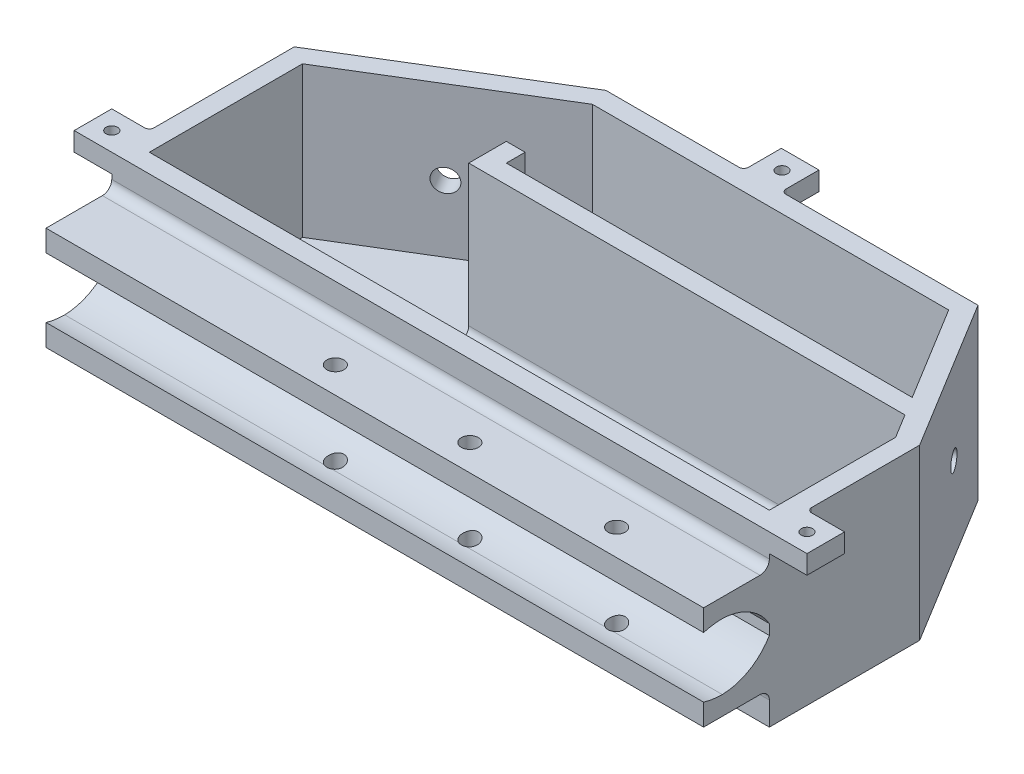
SolidWorks part; units mm, degrees
ref_plane "Front Plane" through (0, 0, 0) normal (0, 0, 1) x (1, 0, 0)
ref_plane "Top Plane" through (0, 0, 0) normal (0, 1, 0) x (1, 0, 0)
ref_plane "Right Plane" through (0, 0, 0) normal (1, 0, 0) x (0, 0, -1)
sketch "Sketch1" plane through (0, 0, 0) normal (0, 1, 0) x (1, 0, 0)
  line L1 (-165, 70) -> (165, 70)
  line L2 (-165, 70) -> (-165, -70)
  line L3 (-165, -70) -> (165, -70)
  line L4 (165, 70) -> (165, -70)
  line L5 (-165, 70) -> (165, -70) construction
  line L6 (-165, -70) -> (165, 70) construction
  line L7 (-175, 80) -> (175, 80)
  line L8 (-175, 80) -> (-175, -80)
  line L9 (-175, -80) -> (175, -80)
  line L10 (175, 80) -> (175, -80)
  line L11 (-175, 80) -> (175, -80) construction
  line L12 (-175, -80) -> (175, 80) construction
  point P0 (0, 0)
  point P6 (0, 0)
  dimension "D1" = 330
  dimension "D2" = 140
  dimension "D3" = 350
  dimension "D4" = 160
extrude "Boss-Extrude1" add sketch "Sketch1" along normal blind 80
sketch "Sketch2" plane through (0, 0, 0) normal (0, -1, 0) x (1, 0, 0)
  line L1 (-175, 80) -> (175, 80)
  line L2 (-175, 80) -> (-175, -80)
  line L3 (-175, -80) -> (175, -80)
  line L4 (175, 80) -> (175, -80)
  line L5 (-175, 80) -> (175, -80) construction
  line L6 (-175, -80) -> (175, 80) construction
  point P0 (0, 0)
extrude "Boss-Extrude2" add sketch "Sketch2" along normal blind 10
sketch "Sketch3" plane through (0, 0, 0) normal (0, 1, 0) x (1, 0, 0)
  line L0 (-165, -70) -> (165, -70) construction
  line L1 (-75, 20) -> (165, 20)
  line L2 (-75, 20) -> (-75, 10)
  line L3 (-75, 10) -> (165, 10)
  line L4 (165, 20) -> (165, 10)
  line L5 (165, -70) -> (165, 70) construction
  dimension "D1" = 240
  dimension "D2" = 10
  dimension "D3" = 80
  dimension "D4" = 0
extrude "Boss-Extrude3" add sketch "Sketch3" along normal up to vertex (80 mm away)
sketch "Sketch4" plane through (0, -10, 0) normal (0, -1, 0) x (1, 0, 0)
  line L0 (165, -70) -> (-165, -70) construction
  line L1 (165, -20) -> (165, -70) construction
  circle A0 centre (115, -45) radius 8.25
  dimension "D1" = 16.5
  dimension "D2" = 25
  dimension "D3" = 50
extrude "Cut-Extrude1" cut sketch "Sketch4" against normal blind 10
sketch "Sketch5" plane through (0, 0, -20) normal (0, 0, -1) x (-1, 0, 0)
  line L0 (-165, 0) -> (75, 0) construction
  line L1 (75, 80) -> (65, 80)
  line L2 (75, 80) -> (75, 0)
  line L3 (75, 0) -> (65, 0)
  line L4 (65, 80) -> (65, 0)
  dimension "D1" = 10
extrude "Boss-Extrude4" add sketch "Sketch5" along normal blind 10
sketch "Sketch6" plane through (-175, 0, 0) normal (-1, 0, 0) x (0, 0, 1)
  line L0 (80, 80) -> (80, -10) construction
  line L1 (80, 62.5) -> (115, 62.5)
  line L2 (80, 62.5) -> (80, 7.5)
  line L3 (80, 7.5) -> (115, 7.5)
  line L4 (115, 62.5) -> (115, 7.5)
  point P9 (80, 35)
  point P10 (80, 35)
  dimension "D1" = 35
  dimension "D2" = 55
extrude "Boss-Extrude5" add sketch "Sketch6" against normal up to vertex (350 mm away)
sketch "Sketch7" plane through (-175, 0, 0) normal (-1, 0, 0) x (0, 0, 1)
  line L0 (115, 62.5) -> (80, 7.5) construction
  line L1 (80, 62.5) -> (115, 7.5) construction
  line L2 (97.5, 35) -> (80, 35) construction
  line L3 (80, 62.5) -> (80, 7.5) construction
  line L4 (80, 32.25) -> (80, 37.75)
  arc A0 (80, 32.25) -> (105.0363, 17.552) centre (105.81, 47.542) ccw
  arc A1 (80, 37.75) -> (104.9636, 52.5519) centre (105.8735, 22.5657) cw
  ellipse E0 centre (104.9999, 35.052) end of major axis (80, 35) minor radius 17.5 (105.0363, 17.552) -> (104.9636, 52.5519) ccw
  point P21 (80, 35)
  dimension "D1" = 50
  dimension "D2" = 35
  dimension "D3" = 5.5
extrude "Cut-Extrude2" cut sketch "Sketch7" against normal through all
sketch "Sketch8" plane through (0, 62.5, 0) normal (0, 1, 0) x (1, 0, 0)
  line L1 (-175, -80) -> (-175, -115) construction
  line L4 (175, -101) -> (-175, -101) construction
  line L5 (175, -115) -> (175, -80) construction
  line L6 (-175, -115) -> (-175, -80) construction
  line L7 (175, -80) -> (-175, -80) construction
  circle A0 centre (-35, -101) radius 4.55
  circle A1 centre (36.6, -101) radius 4.55
  circle A2 centre (114.7, -101) radius 4.55
  dimension "D1" = 9.1
  dimension "D2" = 9.1
  dimension "D3" = 9.1
  dimension "D4" = 21
  dimension "D5" = 71.6
  dimension "D6" = 78.1
  dimension "D7" = 140
extrude "Cut-Extrude3" cut sketch "Sketch8" against normal through all
sketch "Sketch9" plane through (0, 80, 0) normal (0, 1, 0) x (1, 0, 0)
  line L0 (0, 0) -> (0, 80) construction
  line L7 (-175, 80) -> (-175, -80) construction
  line L23 (175, 80) -> (-175, 80) construction
  line L24 (0, 0) -> (175, 0) construction
  line L25 (175, -80) -> (175, 80) construction
  line L30 (175, -80) -> (195, -80)
  line L31 (175, -80) -> (175, -60)
  line L32 (175, -60) -> (195, -60)
  line L33 (195, -80) -> (195, -60)
  line L34 (-195, -80) -> (-195, -60)
  line L35 (-175, -60) -> (-195, -60)
  line L36 (-175, -80) -> (-175, -60)
  line L37 (-175, -80) -> (-195, -80)
  circle A3 centre (185, -70) radius 3.05
  circle A4 centre (-185, -70) radius 3.05
  dimension "D4" = 0
  dimension "D5" = 10
extrude "Boss-Extrude7" add sketch "Sketch9" against normal blind 10
fillet "Fillet1" radius 5 4 edges at (0, 7.5, 80) (0, 62.5, 80) (45, 0, -10) (50, 0, -20)
sketch "Sketch12" plane through (0, 80, 0) normal (0, 1, 0) x (1, 0, 0)
  line L0 (-72.0151, 80) -> (-175, 17.1383)
  line L1 (175, 80) -> (-175, 80) construction
  line L2 (-175, 80) -> (-175, -60) construction
  line L3 (-175, 17.1383) -> (-175, 80)
  line L4 (-175, 80) -> (-72.0151, 80)
  line L5 (175, 80) -> (-175, 80) construction
  point P6 (-175, -40.1221)
  point P9 (-81.3581, 80)
  point P12 (-175, -32.0879)
  point P13 (-90.837, 80)
  point P14 (-175, 17.1383)
  point P15 (-81.4726, 80)
  point P16 (0, 0)
  point P17 (-72.0151, 80)
extrude "Cut-Extrude5" cut sketch "Sketch12" against normal through all
sketch "Sketch13" plane through (-55.1248, 0, -90.3098) normal (-0.521, 0, -0.8536) x (-0.8536, 0, 0.521)
  line L1 (19.7882, -10) -> (140.4426, -10)
  line L2 (19.7882, -10) -> (19.7882, 80)
  line L3 (19.7882, 80) -> (140.4426, 80)
  line L4 (140.4426, -10) -> (140.4426, 80)
extrude "Boss-Extrude8" add sketch "Sketch13" against normal blind 10
sketch "Sketch14" plane through (0, 80, 0) normal (0, 1, 0) x (1, 0, 0)
  line L0 (126.0404, 80) -> (175, 0)
  line L1 (175, 80) -> (-72.0151, 80) construction
  line L2 (175, -60) -> (175, 80) construction
  line L3 (175, 0) -> (175, 80)
  line L4 (175, 80) -> (126.0404, 80)
  line L5 (175, -60) -> (175, 80) construction
  point P6 (175, 38.4785)
  point P10 (175, 36.4408)
  point P11 (126.0404, 80)
  point P12 (175, 20.615)
  point P13 (175, 18.8567)
  point P14 (175, 0)
extrude "Cut-Extrude8" cut sketch "Sketch14" against normal through all
sketch "Sketch15" plane through (127.3155, 0, -77.9165) normal (0.8529, 0, -0.522) x (-0.522, 0, -0.8529)
  line L1 (-91.3498, -10) -> (2.4427, -10)
  line L2 (-91.3498, -10) -> (-91.3498, 80)
  line L3 (-91.3498, 80) -> (2.4427, 80)
  line L4 (2.4427, -10) -> (2.4427, 80)
extrude "Boss-Extrude9" add sketch "Sketch15" against normal blind 10
sketch "Sketch16" plane through (0, 80, 0) normal (0, 1, 0) x (1, 0, 0)
  line L11 (1.381, 80) -> (21.381, 80)
  line L12 (1.381, 80) -> (1.381, 100)
  line L13 (1.381, 100) -> (21.381, 100)
  line L14 (21.381, 80) -> (21.381, 100)
  circle A2 centre (11.718, 90) radius 3.05
  dimension "D8" = 6.1
  dimension "D6" = 20
  dimension "D7" = 20
extrude "Boss-Extrude10" add sketch "Sketch16" against normal blind 10
sketch "Sketch17" plane through (127.3155, 0, -77.9165) normal (0.8529, 0, -0.522) x (-0.522, 0, -0.8529)
  line L0 (-91.3498, -10) -> (-91.3498, 80) construction
  circle A0 centre (-36.3498, 35) radius 5
  dimension "D1" = 10
  dimension "D2" = 55
extrude "Cut-Extrude9" cut sketch "Sketch17" against normal blind 10
sketch "Sketch18" plane through (-55.1248, 0, -90.3098) normal (-0.521, 0, -0.8536) x (-0.8536, 0, 0.521)
  circle A0 centre (79.4943, 35.4233) radius 6
  dimension "D1" = 12
extrude "Cut-Extrude10" cut sketch "Sketch18" against normal blind 10
fillet "Fillet2" radius 2.5 4 edges at (175, 75, 60) (-175, 75, 60) (1.381, 75, -80) (21.381, 75, -80)
sketch "Sketch19" plane through (0, 80, 0) normal (0, 1, 0) x (1, 0, 0)
  line L0 (-175, 17.1383) -> (-175, -57.5) construction
  line L1 (-177.5, -60) -> (-195, -60) construction
  line L2 (-195, -60) -> (-195, -80) construction
  line L3 (-195, -80) -> (195, -80) construction
  line L4 (195, -80) -> (195, -60) construction
  line L5 (195, -60) -> (177.5, -60) construction
  line L6 (175, -57.5) -> (175, 0) construction
  line L7 (126.0404, 80) -> (175, 0) construction
  line L8 (126.0404, 80) -> (23.881, 80) construction
  line L9 (21.381, 82.5) -> (21.381, 100) construction
  line L10 (21.381, 100) -> (1.381, 100) construction
  line L11 (1.381, 100) -> (1.381, 82.5) construction
  line L12 (-1.119, 80) -> (-72.0151, 80) construction
  line L13 (-175, 17.1383) -> (-72.0151, 80) construction
  line L14 (-175, 17.1383) -> (-175, -57.5)
  line L15 (-177.5, -60) -> (-195, -60)
  line L16 (-195, -60) -> (-195, -80)
  line L17 (-195, -80) -> (195, -80)
  line L18 (195, -80) -> (195, -60)
  line L19 (195, -60) -> (177.5, -60)
  line L20 (175, -57.5) -> (175, 0)
  line L21 (126.0404, 80) -> (175, 0)
  line L22 (126.0404, 80) -> (23.881, 80)
  line L23 (21.381, 82.5) -> (21.381, 100)
  line L24 (21.381, 100) -> (1.381, 100)
  line L25 (1.381, 100) -> (1.381, 82.5)
  line L26 (-1.119, 80) -> (-72.0151, 80)
  line L27 (-175, 17.1383) -> (-72.0151, 80)
  arc A0 (-177.5, -60) -> (-175, -57.5) centre (-177.5, -57.5) ccw construction
  circle A1 centre (-185, -70) radius 3.05 construction
  circle A2 centre (185, -70) radius 3.05 construction
  arc A3 (175, -57.5) -> (177.5, -60) centre (177.5, -57.5) ccw construction
  arc A4 (21.381, 82.5) -> (23.881, 80) centre (23.881, 82.5) ccw construction
  circle A5 centre (11.718, 90) radius 3.05 construction
  arc A6 (-1.119, 80) -> (1.381, 82.5) centre (-1.119, 82.5) ccw construction
  arc A7 (-177.5, -60) -> (-175, -57.5) centre (-177.5, -57.5) ccw
  circle A8 centre (-185, -70) radius 3.05
  circle A9 centre (185, -70) radius 3.05
  arc A10 (175, -57.5) -> (177.5, -60) centre (177.5, -57.5) ccw
  arc A11 (21.381, 82.5) -> (23.881, 80) centre (23.881, 82.5) ccw
  circle A12 centre (11.718, 90) radius 3.05
  arc A13 (-1.119, 80) -> (1.381, 82.5) centre (-1.119, 82.5) ccw
sketch "Sketch20" plane through (0, 80, 0) normal (0, 1, 0) x (1, 0, 0)
  line L0 (-70.5573, 61.171) -> (-70.5573, -33.5857) construction
